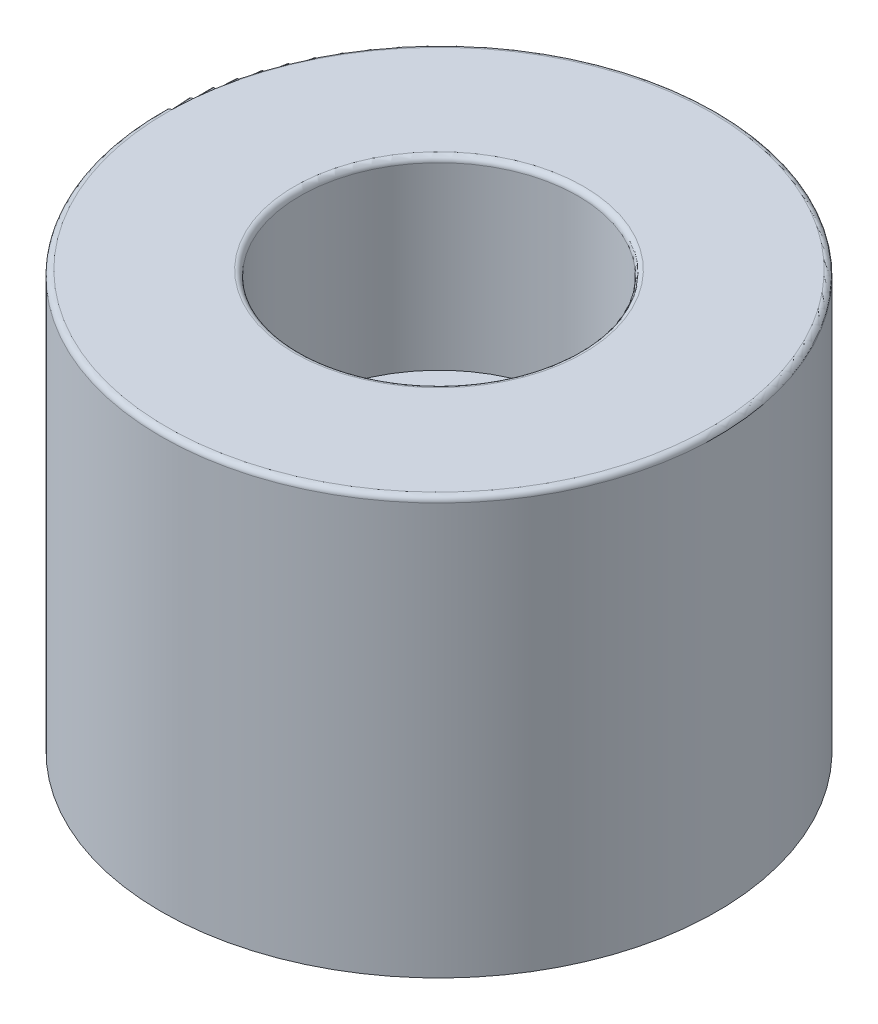
SolidWorks part; units mm, degrees
ref_plane "Front" through (0, 0, 0) normal (0, 0, 1) x (1, 0, 0)
ref_plane "Top" through (0, 0, 0) normal (0, 1, 0) x (1, 0, 0)
ref_plane "Right" through (0, 0, 0) normal (1, 0, 0) x (0, 0, -1)
sketch "Sketch1" plane through (0, 0, 0) normal (0, 0, 1) x (1, 0, 0)
  line L0 (9.525, -7.1438) -> (-9.525, -7.1438) construction
  line L1 (0, -7.1438) -> (0, 7.1438) construction
  line L2 (4.7625, 0.7937) -> (-4.7625, 0.7937) construction
  line L3 (2.3813, -7.1438) -> (-2.3813, -7.1438) construction
  point P7 (0, 0.7937)
  dimension "OD" = 19.05
  dimension "Height" = 14.2875
  dimension "Counterbore Diameter" = 9.525
  dimension "Mounting Surface Height" = 7.9375
  dimension "Mounting Hole Diameter" = 4.7625
sketch "Sketch2" plane through (0, 0, 0) normal (0, 0, 1) x (1, 0, 0)
  line L0 (-9.525, -7.1438) -> (-9.525, 7.1438)
  line L1 (-9.525, 7.1438) -> (-4.7625, 7.1438)
  line L2 (-4.7625, 7.1438) -> (-4.7625, 0.7937)
  line L3 (-4.7625, 0.7937) -> (-2.3813, 0.7937)
  line L4 (4.7625, 0.7937) -> (-4.7625, 0.7937) construction
  line L5 (-2.3813, 0.7937) -> (-2.3813, -7.1438)
  line L6 (-2.3813, -7.1438) -> (-9.525, -7.1438)
revolve "Revolve1" add sketch "Sketch2" angle 360 about L1
fillet "Fillet1" radius 0.1905 1 edges at (0, 7.1438, -4.7625)
sketch "Sketch3" plane through (0, 0, 0) normal (0, 0, 1) x (1, 0, 0)
  line L0 (-2.3813, 0.7937) -> (-2.3813, -7.1438) construction
  line L1 (2.3813, -7.1438) -> (2.3813, 0.7937) construction
  line L2 (-4.7625, 6.9533) -> (-4.7625, 0.7937) construction
  line L3 (4.7625, 0.7937) -> (4.7625, 6.9533) construction
  line L4 (-2.3813, 0.7937) -> (-2.3813, -7.1438)
  line L5 (2.3813, -7.1438) -> (2.3813, 0.7937)
  line L6 (-4.7625, 6.9533) -> (-4.7625, 0.7937)
  line L7 (4.7625, 0.7937) -> (4.7625, 6.9533)
  line L8 (-4.7625, 0.7937) -> (-2.3813, 0.7937)
  line L9 (2.3813, 0.7937) -> (4.7625, 0.7937)
  line L10 (-9.525, -7.1438) -> (9.525, -7.1438) construction
  arc A0 (-4.7625, 6.9533) -> (-4.953, 7.1438) centre (-4.953, 6.9533) ccw construction
  arc A1 (4.953, 7.1438) -> (4.7625, 6.9533) centre (4.953, 6.9533) ccw construction
  arc A2 (-4.7625, 6.9533) -> (-4.953, 7.1438) centre (-4.953, 6.9533) ccw
  arc A3 (4.953, 7.1438) -> (4.7625, 6.9533) centre (4.953, 6.9533) ccw
  dimension "D1" = 9.525
  dimension "D2" = 4.7625
  dimension "D3" = 19.05
fillet "Fillet2" radius 0.1905 1 edges at (0, 7.1438, -9.525)
equation "\"D1@Fillet1\"=\"OD@Sketch1\"*.01"
